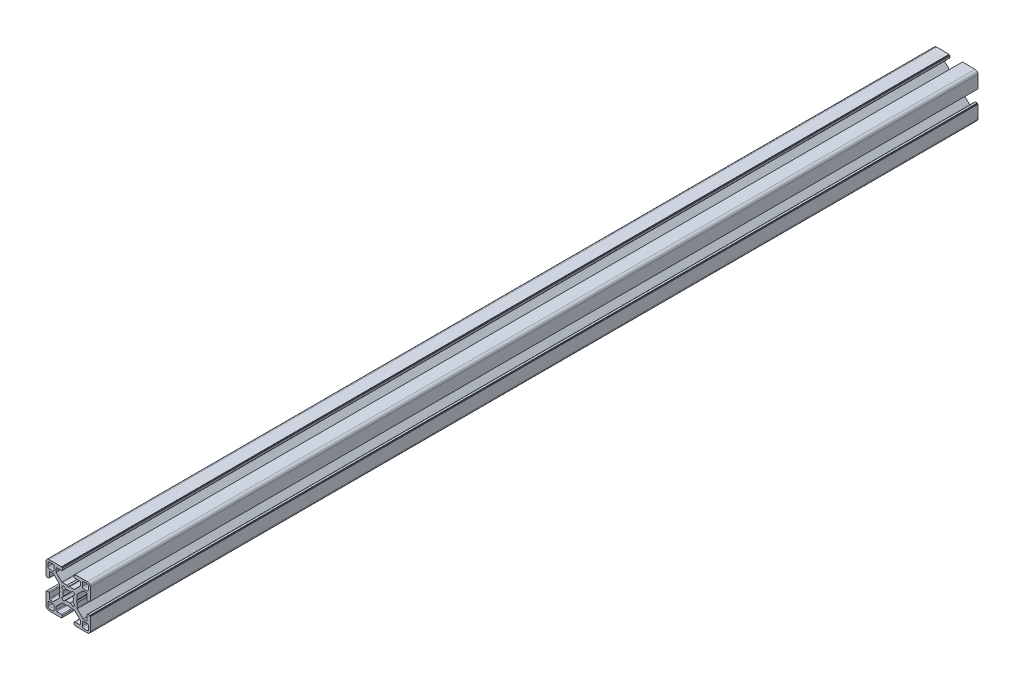
SolidWorks part; units mm, degrees
ref_plane "Front Plane" through (0, 0, 0) normal (0, 0, 1) x (1, 0, 0)
ref_plane "Top Plane" through (0, 0, 0) normal (0, 1, 0) x (1, 0, 0)
ref_plane "Right Plane" through (0, 0, 0) normal (1, 0, 0) x (0, 0, -1)
sketch "Sketch1" plane through (0, 0, 0) normal (0, 0, 1) x (1, 0, 0)
  line L0 (-15, 0) -> (15, 0) construction
  line L1 (0, -15) -> (0, 15) construction
  line L2 (-4.5, 15) -> (4.5, 15) construction
  line L3 (-4, -15) -> (4, -15) construction
  line L4 (-4.5, 15) -> (-4.5, 14.5)
  line L5 (-4.5, 14.5) -> (-4, 14.5)
  line L6 (-4, 14.5) -> (-4, 13.29)
  line L7 (-4.5, 12.79) -> (-7.7675, 12.79)
  line L8 (-8.2675, 12.29) -> (-8.2675, 10.2707)
  line L9 (-8.1211, 9.9171) -> (-4.3504, 6.1464)
  line L10 (-3.9968, 6) -> (0, 6)
  line L11 (0, 0) -> (-15, 15) construction
  line L12 (-4.5, 15) -> (-12.968, 15)
  line L14 (-12.705, 9.5135) -> (-10.5135, 9.5135)
  line L15 (-13.705, 10.5135) -> (-13.705, 12.705)
  line L16 (-12.705, 13.705) -> (-10.5135, 13.705)
  line L17 (-9.5135, 10.5135) -> (-9.5135, 12.705)
  line L18 (-13.705, 9.5135) -> (-9.5135, 13.705) construction
  line L19 (-13.705, 13.705) -> (-9.5135, 9.5135) construction
  line L20 (-3.1568, 4.5038) -> (-1.5303, 3.1477) construction
  line L21 (-4.5038, 3.1568) -> (-3.1477, 1.5303) construction
  line L22 (-6, 3.9968) -> (-6, 0)
  line L23 (-9.9171, 8.1211) -> (-6.1464, 4.3504)
  line L24 (-15, 4.5) -> (-15, 12.968)
  line L25 (-12.29, 8.2675) -> (-10.2707, 8.2675)
  line L26 (-12.79, 4.5) -> (-12.79, 7.7675)
  line L27 (-14.5, 4) -> (-13.29, 4)
  line L28 (-14.5, 4.5) -> (-14.5, 4)
  line L29 (-15, 4.5) -> (-14.5, 4.5)
  circle A0 centre (0, 0) radius 3.5
  arc A1 (-12.968, 15) -> (-15, 12.968) centre (-12.968, 12.968) ccw
  circle A2 centre (0, 0) radius 5.5 construction
  arc A3 (-10.5135, 9.5135) -> (-9.5135, 10.5135) centre (-10.5135, 10.5135) ccw
  arc A4 (-13.705, 12.705) -> (-12.705, 13.705) centre (-12.705, 12.705) cw
  arc A5 (-10.5135, 13.705) -> (-9.5135, 12.705) centre (-10.5135, 12.705) cw
  arc A6 (-12.705, 9.5135) -> (-13.705, 10.5135) centre (-12.705, 10.5135) cw
  arc A7 (-12.79, 4.5) -> (-13.29, 4) centre (-13.29, 4.5) cw
  arc A8 (-12.29, 8.2675) -> (-12.79, 7.7675) centre (-12.29, 7.7675) ccw
  arc A9 (-9.9171, 8.1211) -> (-10.2707, 8.2675) centre (-10.2707, 7.7675) ccw
  arc A10 (-6, 3.9968) -> (-6.1464, 4.3504) centre (-6.5, 3.9968) ccw
  arc A11 (-4.3504, 6.1464) -> (-3.9968, 6) centre (-3.9968, 6.5) ccw
  arc A12 (-4, 13.29) -> (-4.5, 12.79) centre (-4.5, 13.29) cw
  arc A13 (-7.7675, 12.79) -> (-8.2675, 12.29) centre (-7.7675, 12.29) ccw
  arc A14 (-8.2675, 10.2707) -> (-8.1211, 9.9171) centre (-7.7675, 10.2707) ccw
  point P4 (0, 0)
  point P8 (0, 0)
  point P13 (0, 15)
  point P15 (0, -15)
  point P16 (0, 6)
  point P23 (-11.6092, 11.6093)
  point P26 (0, 6)
  point P62 (-12.79, 4)
  point P65 (-12.79, 8.2675)
  point P68 (-10.0636, 8.2675)
  point P71 (-6, 4.2039)
  point P74 (-4.2039, 6)
  point P77 (-4, 12.79)
  point P80 (-8.2675, 12.79)
  point P83 (-8.2675, 10.0636)
  dimension "Center Hole Diameter" = 7
  dimension "D11" = 2.032
  dimension "D9" = 11
  dimension "D13" = 1
  dimension "D14" = 0.5
  dimension "Rail Height" = 30
  dimension "Rail Width" = 30
  dimension "T-Slot Width" = 8
  dimension "T-Slot Depth" = 9
  dimension "D1" = 9
  dimension "D2" = 45
  dimension "D3" = 8
  dimension "D4" = 2.21
  dimension "D5" = 16.535
  dimension "D7" = 2.54
  dimension "D6" = 1.295
  dimension "D8" = 1.246
  dimension "D10" = 10.36
  dimension "D12" = 1.905
sketch "Sketch2" plane through (0, 0, 0) normal (1, 0, 0) x (0, 0, -1)
  line L0 (-76.2, 0) -> (76.2, 0) construction
  line L2 (0, -15) -> (0, 15) construction
  line L3 (0, -15) -> (0, 15) construction
  line L4 (-76.2, -15) -> (-76.2, 15) construction
  line L5 (76.2, -15) -> (76.2, 15) construction
  point P0 (-38.7, 0)
  point P3 (0, 0)
  point P4 (38.7, 0)
  point P12 (-76.2, 0)
  point P14 (76.2, 0)
  dimension "Length" = 152.4
  dimension "D1" = 37.5
sketch "Sketch3" plane through (0, 0, 0) normal (0, 0, 1) x (1, 0, 0)
  line L0 (-4.5038, 3.1568) -> (-3.1477, 1.5303)
  line L1 (0, 3.5) -> (0, 5.5)
  line L2 (-5.5, 0) -> (-3.5, 0)
  line L7 (-6, 3.9968) -> (-6, 0) construction
  line L31 (-9.9171, 8.1211) -> (-6.1464, 4.3504) construction
  line L117 (-12.29, 8.2675) -> (-10.2707, 8.2675) construction
  line L118 (-12.79, 4.5) -> (-12.79, 7.7675) construction
  line L157 (-12.705, 9.5135) -> (-10.5135, 9.5135)
  line L158 (-9.5135, 10.5135) -> (-9.5135, 12.705)
  line L163 (-10.5135, 13.705) -> (-12.705, 13.705)
  line L164 (-13.705, 12.705) -> (-13.705, 10.5135)
  line L165 (-12.705, 9.5135) -> (-10.5135, 9.5135)
  line L166 (-9.5135, 10.5135) -> (-9.5135, 12.705)
  line L167 (-10.5135, 13.705) -> (-12.705, 13.705)
  line L168 (-13.705, 12.705) -> (-13.705, 10.5135)
  line L169 (-14.5, 4) -> (-13.29, 4) construction
  line L170 (-14.5, 4.5) -> (-14.5, 4) construction
  line L171 (-15, 4.5) -> (-14.5, 4.5) construction
  line L172 (-15, 4.5) -> (-15, 12.968) construction
  line L173 (-4.5, 15) -> (-12.968, 15) construction
  line L174 (-4.5, 15) -> (-4.5, 14.5) construction
  line L175 (-4.5, 14.5) -> (-4, 14.5) construction
  line L176 (-4, 14.5) -> (-4, 13.29) construction
  line L177 (-4.5, 12.79) -> (-7.7675, 12.79) construction
  line L178 (-8.2675, 12.29) -> (-8.2675, 10.2707) construction
  line L179 (-8.1211, 9.9171) -> (-4.3504, 6.1464) construction
  line L180 (-3.9968, 6) -> (0, 6) construction
  line L181 (-6, 3.9968) -> (-6, 0.866)
  line L182 (-9.9171, 8.1211) -> (-6.1464, 4.3504)
  line L183 (-12.29, 8.2675) -> (-10.2707, 8.2675)
  line L184 (-12.79, 4.5) -> (-12.79, 7.7675)
  line L185 (-14.5, 4) -> (-13.29, 4)
  line L186 (-14.5, 4.5) -> (-14.5, 4)
  line L187 (-15, 4.5) -> (-14.5, 4.5)
  line L188 (-15, 4.5) -> (-15, 12.968)
  line L189 (-4.5, 15) -> (-12.968, 15)
  line L190 (-4.5, 15) -> (-4.5, 14.5)
  line L191 (-4.5, 14.5) -> (-4, 14.5)
  line L192 (-4, 14.5) -> (-4, 13.29)
  line L193 (-4.5, 12.79) -> (-7.7675, 12.79)
  line L194 (-8.2675, 12.29) -> (-8.2675, 10.2707)
  line L195 (-8.1211, 9.9171) -> (-4.3504, 6.1464)
  line L196 (-3.9968, 6) -> (-0.866, 6)
  line L197 (-0.866, 6) -> (0, 5.5)
  line L198 (0, -15) -> (0, 15) construction
  line L199 (0, 0) -> (-15, 15) construction
  line L200 (0, 0) -> (-15, 15) construction
  line L201 (-3.1568, 4.5038) -> (-1.5303, 3.1477) construction
  line L202 (-3.1568, 4.5038) -> (-1.5303, 3.1477)
  line L203 (-6, 0.866) -> (-5.5, 0)
  line L204 (-15, 0) -> (15, 0) construction
  line L205 (-15, 0) -> (15, 0) construction
  line L206 (0, -15) -> (0, 15) construction
  arc A0 (-3.5, 0) -> (-3.1477, 1.5303) centre (0, 0) cw
  arc A10 (-6, 3.9968) -> (-6.1464, 4.3504) centre (-6.5, 3.9968) ccw construction
  circle A16 centre (0, 0) radius 3.5
  arc A18 (0, 3.5) -> (-1.5303, 3.1477) centre (0, 0) ccw
  arc A20 (-9.9171, 8.1211) -> (-10.2707, 8.2675) centre (-10.2707, 7.7675) ccw construction
  arc A22 (-12.29, 8.2675) -> (-12.79, 7.7675) centre (-12.29, 7.7675) ccw construction
  arc A28 (-13.29, 4) -> (-12.79, 4.5) centre (-13.29, 4.5) ccw construction
  arc A29 (-10.5135, 9.5135) -> (-9.5135, 10.5135) centre (-10.5135, 10.5135) ccw
  arc A30 (-9.5135, 12.705) -> (-10.5135, 13.705) centre (-10.5135, 12.705) ccw
  arc A31 (-12.705, 13.705) -> (-13.705, 12.705) centre (-12.705, 12.705) ccw
  arc A32 (-13.705, 10.5135) -> (-12.705, 9.5135) centre (-12.705, 10.5135) ccw
  arc A33 (-10.5135, 9.5135) -> (-9.5135, 10.5135) centre (-10.5135, 10.5135) ccw
  arc A34 (-9.5135, 12.705) -> (-10.5135, 13.705) centre (-10.5135, 12.705) ccw
  arc A35 (-12.705, 13.705) -> (-13.705, 12.705) centre (-12.705, 12.705) ccw
  arc A36 (-13.705, 10.5135) -> (-12.705, 9.5135) centre (-12.705, 10.5135) ccw
  arc A37 (-12.968, 15) -> (-15, 12.968) centre (-12.968, 12.968) ccw construction
  arc A38 (-4.5, 12.79) -> (-4, 13.29) centre (-4.5, 13.29) ccw construction
  arc A39 (-7.7675, 12.79) -> (-8.2675, 12.29) centre (-7.7675, 12.29) ccw construction
  arc A40 (-8.2675, 10.2707) -> (-8.1211, 9.9171) centre (-7.7675, 10.2707) ccw construction
  arc A41 (-4.3504, 6.1464) -> (-3.9968, 6) centre (-3.9968, 6.5) ccw construction
  arc A42 (-6, 3.9968) -> (-6.1464, 4.3504) centre (-6.5, 3.9968) ccw
  arc A43 (-9.9171, 8.1211) -> (-10.2707, 8.2675) centre (-10.2707, 7.7675) ccw
  arc A44 (-12.29, 8.2675) -> (-12.79, 7.7675) centre (-12.29, 7.7675) ccw
  arc A45 (-13.29, 4) -> (-12.79, 4.5) centre (-13.29, 4.5) ccw
  arc A46 (-12.968, 15) -> (-15, 12.968) centre (-12.968, 12.968) ccw
  arc A47 (-4.5, 12.79) -> (-4, 13.29) centre (-4.5, 13.29) ccw
  arc A48 (-7.7675, 12.79) -> (-8.2675, 12.29) centre (-7.7675, 12.29) ccw
  arc A49 (-8.2675, 10.2707) -> (-8.1211, 9.9171) centre (-7.7675, 10.2707) ccw
  arc A50 (-4.3504, 6.1464) -> (-3.9968, 6) centre (-3.9968, 6.5) ccw
  circle A51 centre (0, 0) radius 5.5 construction
  arc A52 (-3.1568, 4.5038) -> (-4.5038, 3.1568) centre (0, 0) ccw
  dimension "D3" = 60
  dimension "D4" = 60
  dimension "D1" = 0
  dimension "D2" = 0
extrude "Boss-Extrude1" add sketch "Sketch3" along normal mid plane 600
pattern_circular "CirPattern1" count 4 over 360 about axis through (0, 0, 0) along (0, 0, 1) of "Boss-Extrude1"
ref_plane "Contact Plane1" through (15, 0, 0) normal (1, 0, 0) x (0, 0, -1)
ref_plane "Contact Plane2" through (0, -15, 0) normal (0, 1, 0) x (1, 0, 0)
ref_plane "Contact Plane3" through (-15, 0, 0) normal (1, 0, 0) x (0, 0, -1)
ref_plane "Contact Plane4" through (0, 15, 0) normal (0, 1, 0) x (1, 0, 0)
equation "\"D1@Sketch2\" = \"Rail Height@Sketch1\" * 1.25"
equation "\"D1@Sketch1\"=\"T-Slot Width@Sketch1\"+1mm"
equation "\"D3@Sketch1\"=\"T-Slot Width@Sketch1\""
equation "\"D1@Boss-Extrude1\"=\"length\""
equation "\"length\"= 600"
